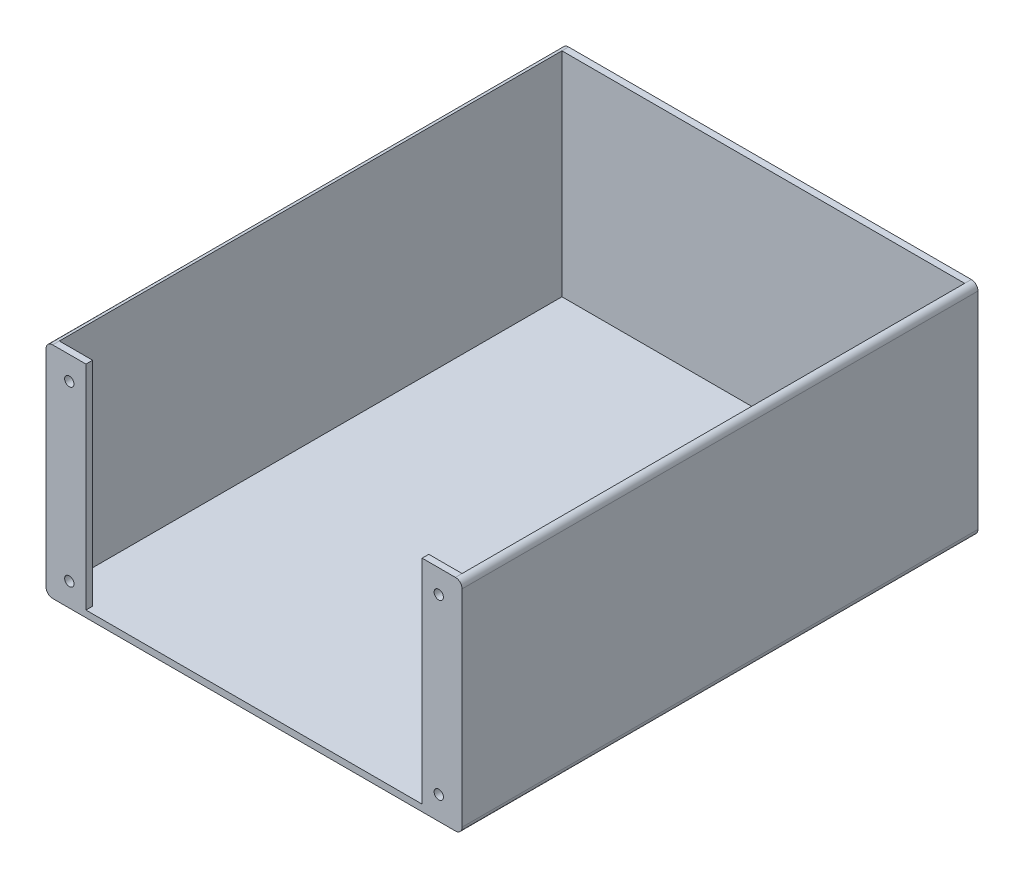
SolidWorks part; units mm, degrees
ref_plane "Front Plane" through (0, 0, 0) normal (0, 0, 1) x (1, 0, 0)
ref_plane "Top Plane" through (0, 0, 0) normal (0, 1, 0) x (1, 0, 0)
ref_plane "Right Plane" through (0, 0, 0) normal (1, 0, 0) x (0, 0, -1)
sketch "Sketch1" plane through (0, 0, 0) normal (0, 0, 1) x (1, 0, 0)
  line L1 (-82.0164, 52.4091) -> (42.9836, 52.4091)
  line L2 (-82.0164, 52.4091) -> (-82.0164, -13.5909)
  line L3 (-82.0164, -13.5909) -> (42.9836, -13.5909)
  line L4 (42.9836, 52.4091) -> (42.9836, -13.5909)
  dimension "D1" = 125
  dimension "D2" = 66
extrude "Boss-Extrude1" add sketch "Sketch1" along normal blind 155
fillet "Fillet1" radius 2 4 edges at (42.9836, -13.5909, 77.5) (42.9836, 52.4091, 77.5) (-82.0164, -13.5909, 77.5) (-82.0164, 52.4091, 77.5)
sketch "Sketch4" plane through (0, 52.4091, 0) normal (0, 1, 0) x (1, 0, 0)
  line L0 (-82.0164, -155) -> (-82.0164, 0) construction
  line L1 (-80.0164, -2) -> (40.9836, -2)
  line L2 (-80.0164, -2) -> (-80.0164, -153)
  line L3 (-80.0164, -153) -> (40.9836, -153)
  line L4 (40.9836, -2) -> (40.9836, -153)
  line L5 (42.9836, 0) -> (42.9836, -155) construction
  line L6 (40.9836, 0) -> (-80.0164, 0) construction
  dimension "D1" = 2
  dimension "D2" = 2
  dimension "D3" = 2
  dimension "D4" = 2
sketch "Sketch7" plane through (0, 0, 155) normal (0, 0, 1) x (1, 0, 0)
  line L0 (-82.0164, 50.4091) -> (-82.0164, -11.5909) construction
  line L1 (40.9836, 52.4091) -> (-80.0164, 52.4091) construction
  line L2 (42.9836, -11.5909) -> (42.9836, 50.4091) construction
  line L3 (-80.0164, -13.5909) -> (40.9836, -13.5909) construction
  circle A0 centre (-75.0164, 45.4091) radius 1.4
  circle A1 centre (-75.0164, -6.5909) radius 1.4
  circle A2 centre (35.9836, -6.5909) radius 1.4
  circle A3 centre (35.9836, 45.4091) radius 1.4
  dimension "D1" = 7
  dimension "D2" = 7
  dimension "D3" = 7
  dimension "D4" = 7
extrude "Cut-Extrude4" cut sketch "Sketch7" against normal blind 15
extrude "Cut-Extrude5" cut sketch "Sketch4" against normal blind 64
sketch "Sketch8" plane through (0, 0, 155) normal (0, 0, 1) x (1, 0, 0)
  line L0 (-82.0164, 50.4091) -> (-82.0164, -11.5909) construction
  line L1 (-70.0164, 52.4405) -> (30.9836, 52.4405)
  line L2 (-70.0164, 52.4405) -> (-70.0164, -11.5909)
  line L3 (-70.0164, -11.5909) -> (30.9836, -11.5909)
  line L4 (30.9836, 52.4405) -> (30.9836, -11.5909)
  line L5 (42.9836, -11.5909) -> (42.9836, 50.4091) construction
  line L6 (-80.0164, -13.5909) -> (40.9836, -13.5909) construction
  dimension "D1" = 12
  dimension "D2" = 12
  dimension "D3" = 2
extrude "Cut-Extrude6" cut sketch "Sketch8" against normal blind 64
